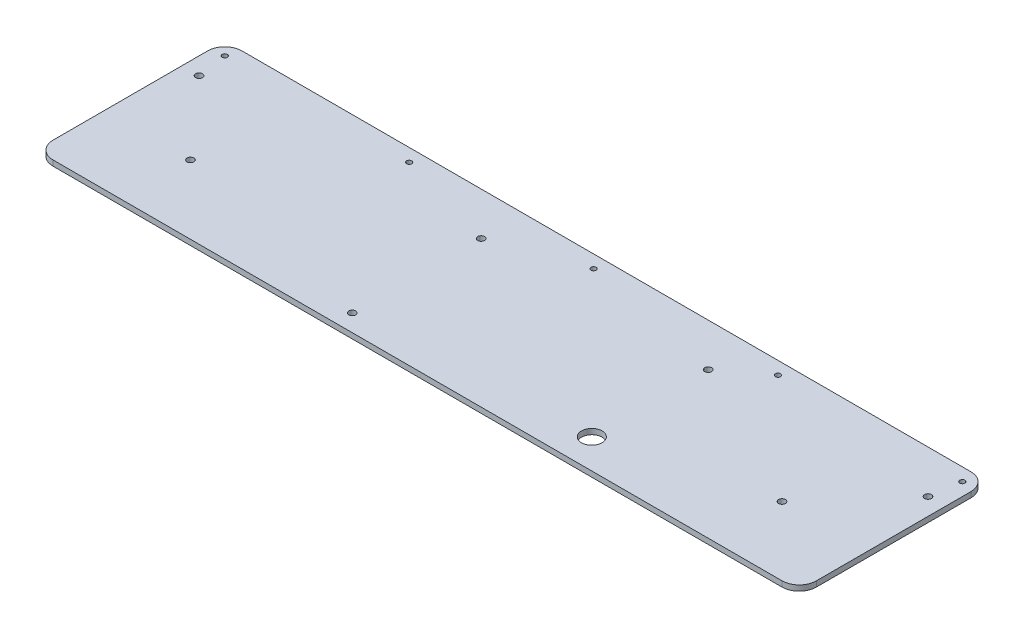
SolidWorks part; units mm, degrees
ref_plane "Front" through (0, 0, 0) normal (0, 0, 1) x (1, 0, 0)
ref_plane "Top" through (0, 0, 0) normal (0, 1, 0) x (1, 0, 0)
ref_plane "Right" through (0, 0, 0) normal (1, 0, 0) x (0, 0, -1)
sketch "Sketch1" plane through (0, 0, 0) normal (0, 1, 0) x (1, 0, 0)
  line L0 (-26.7996, 0) -> (-26.7996, 40)
  line L1 (-26.7996, 0) -> (417.7004, 0)
  line L2 (-26.7996, 0) -> (-26.7996, 110)
  line L3 (-26.7996, 110) -> (417.7004, 110)
  line L4 (417.7004, 0) -> (417.7004, 110)
  line L5 (-26.7996, 40) -> (23.2004, 40)
  line L6 (417.7004, 0) -> (417.7004, 40)
  line L7 (417.7004, 40) -> (367.7004, 40)
  line L8 (23.2004, 40) -> (103.2004, 40)
  line L9 (367.7004, 40) -> (191.7004, 40)
  line L10 (-26.7996, 110) -> (-26.7996, 85)
  line L11 (-26.7996, 85) -> (417.7004, 85)
  line L12 (-26.7996, 85) -> (-16.7996, 85)
  line L13 (417.7004, 85) -> (407.7004, 85)
  line L14 (103.2004, 40) -> (191.7004, 40)
  line L15 (147.4504, 40) -> (147.4504, 85)
  line L16 (279.7004, 40) -> (279.7004, 85)
  line L17 (147.4504, 40) -> (147.4504, 10)
  line L18 (-26.7996, 110) -> (-26.7996, 102.5)
  line L19 (-26.7996, 102.5) -> (417.7004, 102.5)
  line L20 (-26.7996, 102.5) -> (-19.2996, 102.5)
  line L21 (417.7004, 102.5) -> (410.2004, 102.5)
  line L22 (195.4504, 102.5) -> (410.2004, 102.5)
  line L23 (-19.2996, 102.5) -> (195.4504, 102.5)
  line L24 (417.7004, 0) -> (417.7004, 17.2282)
  line L25 (417.7004, 17.2282) -> (279.7004, 17.2282)
  circle A10 centre (367.7004, 40) radius 2
  circle A11 centre (23.2004, 40) radius 2
  circle A25 centre (-16.7996, 85) radius 2
  circle A26 centre (407.7004, 85) radius 2
  circle A27 centre (147.4504, 85) radius 2
  circle A28 centre (279.7004, 85) radius 2
  circle A29 centre (147.4504, 10) radius 2
  circle A30 centre (195.4504, 102.5) radius 1.5
  circle A31 centre (-19.2996, 102.5) radius 1.5
  circle A32 centre (410.2004, 102.5) radius 1.5
  circle A33 centre (302.8254, 102.5) radius 1.5
  circle A34 centre (88.0754, 102.5) radius 1.5
  circle A35 centre (279.7004, 17.2282) radius 6
  dimension "D3" = 40
  dimension "D7" = 80
  dimension "D8" = 176
  dimension "D9" = 25
  dimension "D11" = 10
  dimension "D12" = 30
  dimension "D13" = 7.5
  dimension "D14" = 7.5
  dimension "D16" = 17.2282
  dimension "D1" = 110
  dimension "D2" = 444.5
  dimension "D4" = 50
  dimension "D5" = 40
  dimension "D6" = 50
  dimension "D10" = 10
  dimension "D15" = 7.5
  dimension "D17" = 138
extrude "Boss-Extrude1" add sketch "Sketch1" along normal blind 3.175
fillet "Fillet1" radius 10 4 edges at (417.7004, 1.5875, -110) (417.7004, 1.5875, 0) (-26.7996, 1.5875, 0) (-26.7996, 1.5875, -110)
sketch "Sketch2" plane through (0, 3.175, 0) normal (0, 1, 0) x (1, 0, 0)
  line L0 (23.2004, 40) -> (16.1294, 32.9289)
  line L1 (147.4504, 47.5) -> (152.4504, 47.5)
  line L2 (392.9712, 57.8148) -> (377.6816, 40.6139)
  line L3 (383.9634, 65.8218) -> (369.7169, 49.7946)
  line L4 (9732.2026, 3263.3975) -> (9728.9552, 3272.8555)
  line L5 (147.4504, 47.5) -> (142.4504, 47.5)
  line L6 (322.4478, 33.4546) -> (294.4087, 26.1989)
  line L7 (152.4504, 47.5) -> (152.4504, 76.3397)
  line L8 (-16.7996, 0) -> (407.7004, 0) construction
  line L9 (147.4504, 10) -> (147.4504, 0)
  line L10 (152.4504, 47.5) -> (152.4504, 18.6603)
  line L11 (142.4504, 47.5) -> (142.4504, 76.3397)
  line L12 (142.4504, 47.5) -> (142.4504, 18.6603)
  line L13 (147.4504, 10) -> (147.4504, 85)
  line L14 (147.4504, 85) -> (279.7004, 85)
  line L15 (279.7004, 85) -> (279.7004, 17.2282)
  line L16 (262.617, 15) -> (156.1107, 15)
  line L17 (147.4504, 85) -> (-16.7996, 85)
  line L18 (-16.7996, 85) -> (23.2004, 40)
  line L19 (279.7004, 85) -> (407.7004, 85)
  line L20 (65.3254, 85) -> (65.3254, 80)
  line L21 (65.3254, 80) -> (-8.1393, 80)
  line L22 (65.3254, 80) -> (138.7902, 80)
  line L23 (156.1107, 80) -> (271.0402, 80)
  line L24 (288.3607, 80) -> (399.0402, 80)
  line L25 (279.7004, 51.1141) -> (274.7004, 51.1141)
  line L26 (279.7004, 51.1141) -> (284.7004, 51.1141)
  line L27 (274.7004, 51.1141) -> (274.7004, 33.7148)
  line L28 (274.7004, 76.3397) -> (274.7004, 51.1141)
  line L29 (284.7004, 76.3397) -> (284.7004, 51.1141)
  line L30 (86.4989, 29.8603) -> (32.7923, 42.8277)
  line L31 (86.4989, 29.8603) -> (140.2056, 16.8929)
  line L32 (3.2004, 62.5) -> (6.9375, 65.8218)
  line L33 (23.2004, 40) -> (147.4504, 10)
  line L34 (85.3254, 25) -> (86.4989, 29.8603)
  line L35 (284.7004, 51.1141) -> (284.7004, 33.7148)
  line L36 (279.7004, 17.2282) -> (367.7004, 40)
  line L37 (367.7004, 40) -> (407.7004, 85)
  line L38 (383.9634, 65.8218) -> (398.2098, 81.8491)
  line L39 (383.9634, 65.8218) -> (387.7004, 62.5)
  line L40 (392.9712, 57.8148) -> (387.7004, 62.5)
  line L41 (392.9712, 57.8148) -> (407.7004, 75)
  line L42 (322.4478, 33.4546) -> (323.7004, 28.6141)
  line L43 (324.953, 23.7735) -> (323.7004, 28.6141)
  line L44 (324.953, 23.7735) -> (360.5689, 32.9899)
  line L45 (322.4478, 33.4546) -> (358.0637, 42.671)
  line L46 (324.953, 23.7735) -> (296.9139, 16.5178)
  line L47 (3.2004, 62.5) -> (-0.5366, 59.1782)
  line L48 (-0.5366, 59.1782) -> (13.7098, 43.1509)
  line L49 (-0.5366, 59.1782) -> (-14.7831, 75.2054)
  line L50 (6.9375, 65.8218) -> (21.1839, 49.7946)
  line L51 (6.9375, 65.8218) -> (-7.309, 81.8491)
  line L52 (85.3254, 25) -> (84.1182, 20)
  line L53 (84.1182, 20) -> (30.3293, 32.9872)
  line L54 (84.1182, 20) -> (137.907, 7.0128)
  line L55 (296.7839, 15) -> (407.7004, 15)
  line L56 (407.7004, 10) -> (402.7004, 10)
  line L57 (402.7004, 10) -> (402.7004, 76.3397)
  line L58 (367.7004, 40) -> (407.7004, 10)
  line L59 (390.7004, 29) -> (384.7004, 21)
  line L60 (23.2004, 40) -> (147.4504, 85)
  line L61 (83.5146, 67.5) -> (87.1363, 57.5)
  line L62 (83.5146, 67.5) -> (29.3522, 47.8839)
  line L63 (83.5146, 67.5) -> (137.5997, 86.7214)
  line L64 (87.1363, 57.5) -> (141.2986, 77.1161)
  line L65 (87.1363, 57.5) -> (32.974, 37.8839)
  line L66 (279.7004, 85) -> (367.7004, 40)
  line L67 (326.2572, 67.5) -> (321.1436, 57.5)
  line L68 (284.5105, 76.2328) -> (357.7767, 38.7672)
  line L69 (326.2572, 67.5) -> (289.5511, 86.7214)
  line L70 (326.2572, 67.5) -> (362.8903, 48.7672)
  line L71 (147.4504, 85) -> (279.7004, 17.2282)
  line L72 (211.0132, 46.1141) -> (262.6441, 19.6557)
  line L73 (216.1377, 56.1141) -> (211.0132, 46.1141)
  line L74 (211.0132, 46.1141) -> (152.2503, 76.2273)
  line L75 (216.1377, 56.1141) -> (157.3748, 86.2273)
  line L76 (216.1377, 56.1141) -> (267.7687, 29.6557)
  line L77 (147.4504, 10) -> (279.7004, 85)
  line L78 (211.1089, 51.8493) -> (216.0419, 43.1507)
  line L79 (211.1089, 51.8493) -> (269.7004, 85)
  line L80 (216.0419, 43.1507) -> (274.7004, 76.3397)
  line L81 (211.1089, 51.8493) -> (152.4504, 18.6603)
  line L82 (216.0419, 43.1507) -> (157.4504, 10)
  line L83 (-16.7996, 85) -> (-16.7996, 10)
  line L84 (-16.7996, 10) -> (147.4504, 10)
  line L85 (147.4504, 10) -> (417.7004, 10)
  line L86 (407.7004, 85) -> (407.7004, 10)
  line L87 (-16.7996, 10) -> (-16.7996, 15)
  line L88 (-16.7996, 10) -> (-11.7996, 10)
  line L89 (-16.7996, 15) -> (138.7902, 15)
  line L90 (-11.7996, 10) -> (-11.7996, 76.3397)
  line L91 (390.7004, 29) -> (377.6816, 39.3861)
  line L92 (384.7004, 21) -> (371.6286, 30.8038)
  line L93 (384.7004, 21) -> (399.3671, 10)
  line L94 (390.7004, 29) -> (407.7004, 16.25)
  line L95 (23.2004, 40) -> (-16.7996, 10)
  line L96 (0.2004, 29) -> (6.2004, 21)
  line L97 (0.2004, 29) -> (13.2722, 38.8038)
  line L98 (0.2004, 29) -> (-16.7996, 16.25)
  line L99 (6.2004, 21) -> (19.2722, 30.8038)
  line L100 (6.2004, 21) -> (-8.4662, 10)
  circle A5 centre (147.4504, 85) radius 10
  circle A8 centre (279.7004, 85) radius 10
  circle A19 centre (147.4504, 10) radius 10
  circle A21 centre (23.2004, 40) radius 10
  circle A22 centre (9732.2026, 3263.3975) radius 10
  circle A24 centre (-16.7996, 85) radius 10
  circle A25 centre (407.7004, 85) radius 10
  circle A26 centre (279.7004, 17.2282) radius 17.2282
  circle A27 centre (367.7004, 40) radius 10
  point P84 (213.5754, 13.6141)
  point P91 (85.3254, 62.5)
  point P98 (323.7004, 62.5)
  point P100 (321.1436, 57.5)
  point P106 (213.5754, 51.1141)
  point P109 (213.5754, 47.5)
  point P114 (211.0132, 46.1141)
  point P115 (213.5754, 47.5)
  point P128 (387.7004, 25)
  point P135 (3.2004, 25)
  dimension "D7" = 5
  dimension "D2" = 5
  dimension "D9" = 5
  dimension "D20" = 10
  dimension "D1" = 10
  dimension "D6" = 5
  dimension "D3" = 5
  dimension "D4" = 5
  dimension "D5" = 5
  dimension "D8" = 5
  dimension "D10" = 5
  dimension "D11" = 5
  dimension "D12" = 5
  dimension "D13" = 5
  dimension "D14" = 10
  dimension "D15" = 10
  dimension "D16" = 10
  dimension "D17" = 10
  dimension "D18" = 5
  dimension "D19" = 5
  dimension "D21" = 10
equation "\"width\"=8.66025"
equation "\"supw\"=5"
